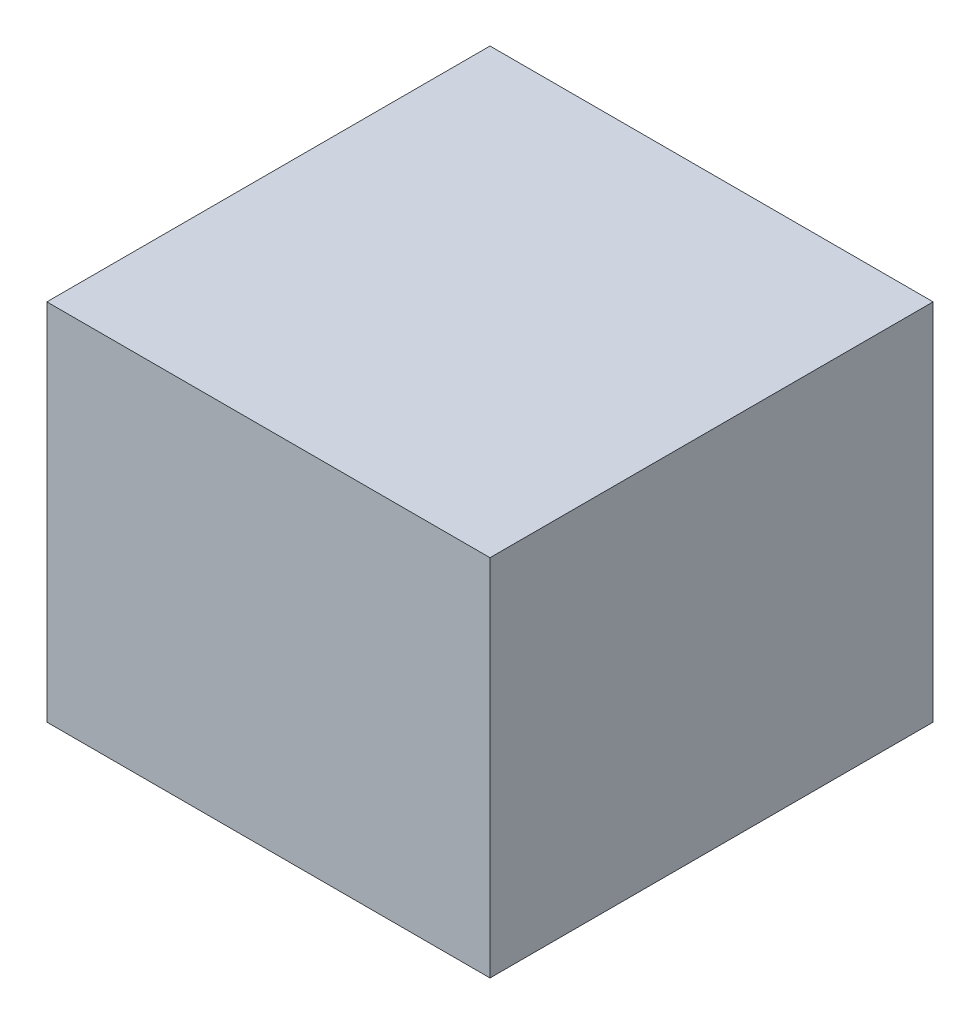
SolidWorks part; units mm, degrees
ref_plane "Front Plane" through (0, 0, 0) normal (0, 0, 1) x (1, 0, 0)
ref_plane "Top Plane" through (0, 0, 0) normal (0, 1, 0) x (1, 0, 0)
ref_plane "Right Plane" through (0, 0, 0) normal (1, 0, 0) x (0, 0, -1)
sketch "Sketch1" plane through (0, 0, 0) normal (0, 1, 0) x (1, 0, 0)
  circle A0 centre (0, 0) radius 16
  circle A1 centre (0, 0) radius 6.25
extrude "Boss-Extrude1" add sketch "Sketch1" along normal blind 100
sketch "Sketch2" plane through (0, 0, 0) normal (0, 0, 1) x (1, 0, 0)
  line L1 (-20, -2) -> (20, -2)
  line L2 (-20, -2) -> (-20, 53)
  line L3 (-20, 53) -> (20, 53)
  line L4 (20, -2) -> (20, 53)
extrude "Cut-Extrude1" cut sketch "Sketch2" against normal mid plane 40
sketch "Sketch3" plane through (0, 0, 0) normal (0, 0, 1) x (1, 0, 0)
  line L1 (-28, 54) -> (28, 54)
  line L2 (-28, 54) -> (-28, 100)
  line L3 (-28, 100) -> (28, 100)
  line L4 (28, 54) -> (28, 100)
extrude "Boss-Extrude2" add sketch "Sketch3" along normal mid plane 56
sketch "Sketch4" plane through (0, 0, 0) normal (0, 0, 1) x (1, 0, 0)
  circle A0 centre (0, 76) radius 8
extrude "Boss-Extrude3" add sketch "Sketch4" along normal mid plane 52
